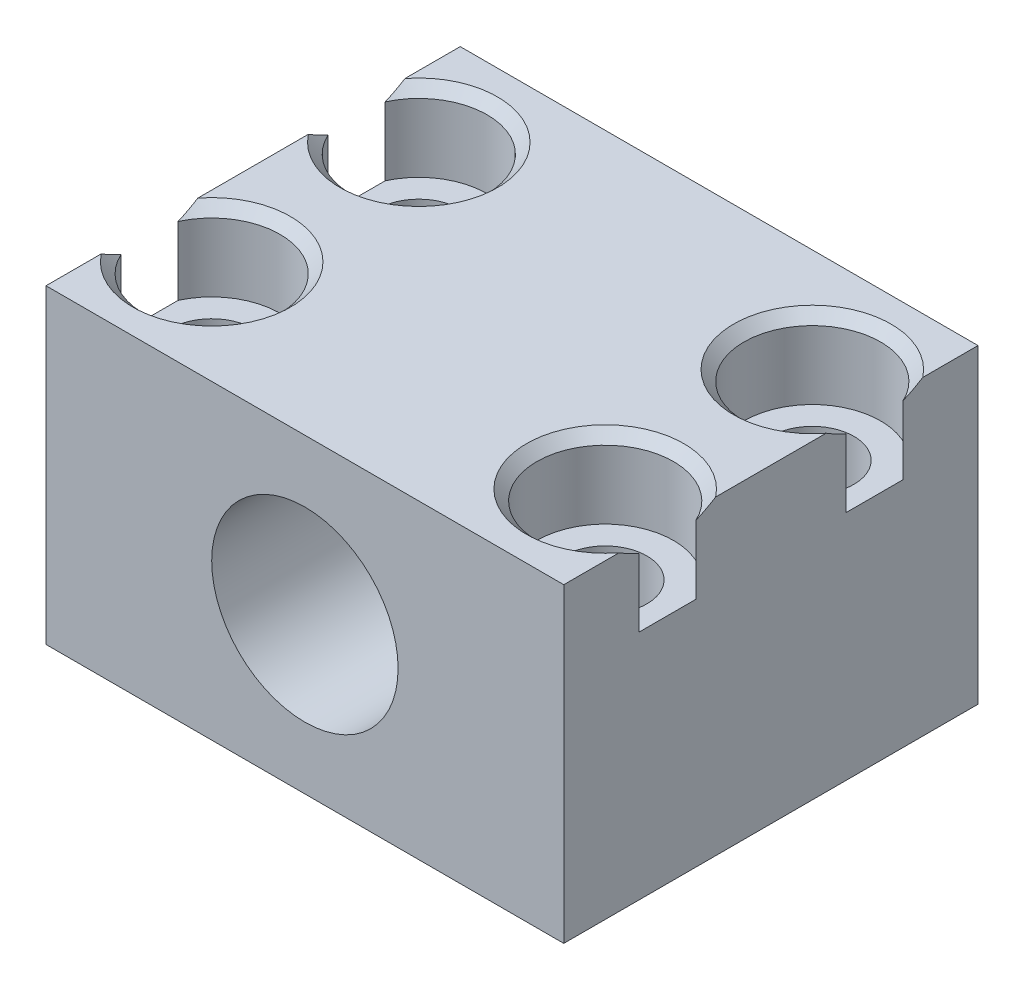
SolidWorks part; units mm, degrees
material "Gray Cast Iron"
ref_plane "Front Plane" through (0, 0, 0) normal (0, 0, 1) x (1, 0, 0)
ref_plane "Top Plane" through (0, 0, 0) normal (0, 1, 0) x (1, 0, 0)
ref_plane "Right Plane" through (0, 0, 0) normal (1, 0, 0) x (0, 0, -1)
sketch "Sketch1" plane through (0, 0, 0) normal (0, 0, 1) x (1, 0, 0)
  circle A0 centre (0, 0) radius 5.715
  circle A1 centre (0, 0) radius 18.669
  dimension "D3" = 11.43
  dimension "D1" = 37.338
extrude "nut-body-extrude" add sketch "Sketch1" along normal blind 25.4
sketch "Sketch2" plane through (0, 0, 0) normal (0, 0, 1) x (1, 0, 0)
  line L0 (0, 9.525) -> (0, 34.8179) construction
  line L1 (9.525, 0) -> (42.4926, 0) construction
  line L3 (-15.875, 9.525) -> (15.875, 9.525)
  line L4 (-15.875, 9.525) -> (-15.875, -9.525)
  line L5 (-15.875, -9.525) -> (15.875, -9.525)
  line L6 (15.875, 9.525) -> (15.875, -9.525)
  circle A1 centre (0, 0) radius 18.669
  circle A2 centre (0, 0) radius 18.669
  point P8 (-15.875, 0)
  point P9 (0, 9.525)
  dimension "D1" = 19.05
  dimension "D3" = 31.75
  dimension "D2" = 0
extrude "nut-trim-cut-extrude" cut sketch "Sketch2" along normal through all contours L3 A2 | L5 A2 | L6 A2 | L4 A2
hole_wizard "CBORE for #10 Socket Head Cap Screw1" positions "Sketch5" profile "Sketch4" counterbore size "#10" standard "ANSI Inch" end condition through all
sketch "Sketch5" plane through (0, 9.525, 0) normal (0, 1, 0) x (1, 0, 0)
  line L0 (12.065, -6.35) -> (12.065, -19.05) construction
  line L1 (12.065, -19.05) -> (-12.065, -19.05) construction
  line L2 (-12.065, -19.05) -> (-12.065, -6.35) construction
  line L3 (-12.065, -6.35) -> (12.065, -6.35) construction
  line L4 (0, 0) -> (0, -12.7) construction
  line L5 (0, -12.7) -> (15.875, -12.7) construction
  line L6 (15.875, -25.4) -> (15.875, 0) construction
  line L7 (-5.715, 0) -> (-5.715, -25.4) construction
  line L8 (-5.715, 0) -> (-5.715, -25.4) construction
  line L9 (5.715, 0) -> (5.715, -25.4) construction
  point P0 (12.065, -6.35)
  point P2 (12.065, -19.05)
  point P4 (-12.065, -19.05)
  point P6 (-12.065, -6.35)
  point P29 (12.065, -12.7)
  point P43 (0, -6.35)
  dimension "D1" = 24.13
  dimension "D2" = 12.7
sketch "Sketch4" plane through (12.065, 9.525, 6.35) normal (1, 0, 0) x (0, 0, 1)
  line L0 (0, 0) -> (0, 19.05)
  line L1 (0, 19.05) -> (2.5527, 19.05)
  line L3 (2.5527, 19.05) -> (2.5527, 4.826)
  line L4 (4.191, 4.826) -> (2.5527, 4.826)
  line L5 (4.191, 4.826) -> (4.191, 0.635)
  line L6 (4.191, 0.635) -> (4.826, 0)
  line L7 (4.826, 0) -> (0, 0)
  line L8 (-4.191, 0.635) -> (-4.826, 0) construction
  line L11 (0, -6.35) -> (0, 107.95) construction
  dimension "Thru Hole Dia." = 5.1054
  dimension "Thru Hole Depth" = 19.05
  dimension "C'Bore Dia." = 8.382
  dimension "C'Bore Depth" = 4.826
  dimension "Near C'Sink Dia." = 9.652
  dimension "Near C'Sink Angle" = 90
equation "\"dovetail-angle\" = 60"
equation "\"dovetail-stock-width\" = 5"
equation "\"dovetail-stock-height\" = 1.25"
equation "\"dovetail-depth\" = 0.5 * \"dovetail-stock-height\""
equation "\"dovetail-throat-width\" = \"dovetail-stock-width\" - (2 * \"dovetail-depth\")"
equation "\"delta-x\" = 6"
equation "\"delta-y\" = 3"
equation "\"gib-thickness\" = 0.25"
equation "\"x-slide-length\" = \"dovetail-stock-width\" + \"delta-x\""
equation "\"y-slide-length\" = \"dovetail-stock-width\" + \"delta-y\""
equation "\"dog-point-diam\" = .149"
equation "\"dog-point-length\" = .067"
equation "\"dovetail-double-height\" = 2 * \"dovetail-depth\" + 0.5"
equation "\"acme-major-diam\" = .5"
equation "\"acme-pitch-diam\" = 0.45"
equation "\"acme-minor-diam\" = 0.4"
equation "\"acme-nut-od\" = 1.47"
equation "\"acme-nut-length\" = 1"
equation "\"D3@Sketch1\"=\"acme-pitch-diam\""
equation "\"D1@Sketch1\"=\"acme-nut-od\""
equation "\"D1@nut-body-extrude\"=\"acme-nut-length\""
equation "\"acme-nut-trim-height\" = .75"
equation "\"D1@Sketch2\"=\"acme-nut-trim-height\""
equation "\"screw-bearing-od\" = 0.5"
equation "\"screw-bearing-length\" = .375"
equation "\"screw-bearing-id\" = .3125"
equation "\"end-plate-thickness\" = \"screw-bearing-length\""
equation "\"screw-add-length\" = 2 * \"end-plate-thickness\" + 1 + 0.5"
equation "\"x-screw-length\" = \"x-slide-length\" + \"screw-add-length\""
equation "\"y-screw-length\" = \"y-slide-length\" + \"screw-add-length\""
equation "\"acme-nut-mount-hole-space-vert\" = 0.5 * \"acme-nut-length\""
equation "\"D2@Sketch5\"=\"acme-nut-mount-hole-space-vert\""
equation "\"vise-hole-center-dist\" = 6.75"
equation "\"wiper_plate_clearance\" = .03"
equation "\"dial-width\" = 0.5"
equation "\"quarter-twenty-free-fit\" = .2667"
equation "\"acme-nut-mount-hole-space-horz\" = 0.95"
equation "\"D1@Sketch5\"=\"acme-nut-mount-hole-space-horz\""
equation "\"acme-nut-trim-width\" = 1.25"
equation "\"acme_nut_clearance\" = .02"
equation "\"dovetail_male_clearance\" = .02"
